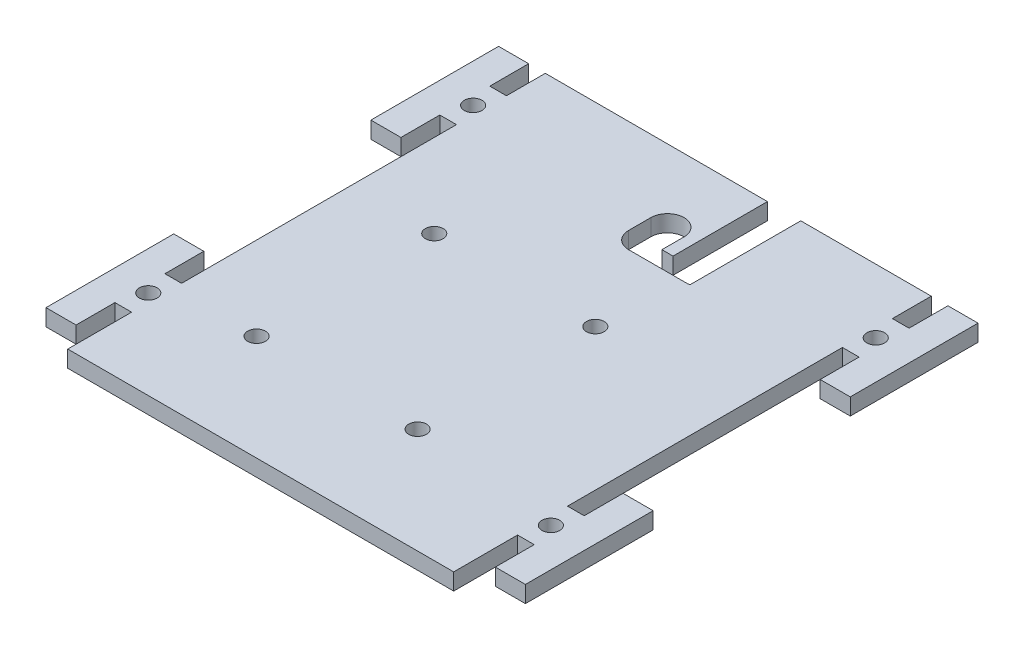
SolidWorks part; units mm, degrees
ref_plane "前视基准面" through (0, 0, 0) normal (0, 0, 1) x (1, 0, 0)
ref_plane "上视基准面" through (0, 0, 0) normal (0, 1, 0) x (1, 0, 0)
ref_plane "右视基准面" through (0, 0, 0) normal (1, 0, 0) x (0, 0, -1)
other "Configuration Table"
sketch "草图1" plane through (0, 0, 0) normal (0, 1, 0) x (1, 0, 0)
  line L0 (-25.4238, 10.5123) -> (44.0762, 10.5123)
  line L1 (44.0762, 10.5123) -> (44.0762, 22.0123)
  line L2 (44.0762, 22.0123) -> (47.0762, 22.0123)
  line L3 (47.0762, 22.0123) -> (47.0762, 15.0123)
  line L4 (47.0762, 15.0123) -> (52.4909, 15.0123)
  line L5 (52.4909, 15.0123) -> (52.4909, 38.0123)
  line L6 (52.4909, 38.0123) -> (47.0762, 38.0123)
  line L7 (47.0762, 38.0123) -> (47.0762, 31.0123)
  line L8 (47.0762, 31.0123) -> (44.0762, 31.0123)
  line L9 (44.0762, 31.0123) -> (44.0762, 80.5123)
  line L10 (44.0762, 80.5123) -> (47.0762, 80.5123)
  line L11 (47.0762, 80.5123) -> (47.0762, 73.5123)
  line L12 (47.0762, 73.5123) -> (52.4909, 73.5123)
  line L13 (52.4909, 73.5123) -> (52.4909, 96.5123)
  line L14 (52.4909, 96.5123) -> (47.0762, 96.5123)
  line L15 (47.0762, 96.5123) -> (47.0762, 89.5123)
  line L16 (47.0762, 89.5123) -> (44.0762, 89.5123)
  line L17 (44.0762, 89.5123) -> (44.0762, 96.5123)
  line L18 (44.0762, 96.5123) -> (20.5762, 96.5123)
  line L20 (19.9909, 76.5089) -> (9.5762, 76.5089)
  line L21 (6.5762, 79.5089) -> (6.5762, 83.5089)
  line L22 (12.5762, 83.5089) -> (12.5762, 79.5089)
  line L23 (12.5762, 79.5089) -> (14.5762, 79.5089)
  line L26 (20.5762, 96.5123) -> (20.5762, 76.5665)
  line L27 (14.5762, 79.5089) -> (14.5762, 96.5123)
  line L28 (14.5762, 96.5123) -> (-25.4238, 96.5123)
  line L29 (44.0762, 10.5123) -> (9.3262, 10.5123) construction
  line L30 (9.3262, 10.5123) -> (9.3262, 36.3757) construction
  line L31 (9.3262, 36.3757) -> (9.3262, 103.0112) construction
  line L32 (-25.4238, 31.0123) -> (-25.4238, 80.5123)
  line L33 (-25.4238, 10.5123) -> (-25.4238, 22.0123)
  line L34 (-25.4238, 22.0123) -> (-28.4238, 22.0123)
  line L35 (-28.4238, 22.0123) -> (-28.4238, 15.0123)
  line L36 (-28.4238, 15.0123) -> (-33.8386, 15.0123)
  line L37 (-33.8386, 15.0123) -> (-33.8386, 38.0123)
  line L38 (-33.8386, 38.0123) -> (-28.4238, 38.0123)
  line L39 (-28.4238, 38.0123) -> (-28.4238, 31.0123)
  line L40 (-28.4238, 31.0123) -> (-25.4238, 31.0123)
  line L41 (-28.4238, 80.5123) -> (-28.4238, 73.5123)
  line L42 (-28.4238, 73.5123) -> (-33.8386, 73.5123)
  line L43 (-25.4238, 80.5123) -> (-28.4238, 80.5123)
  line L44 (-28.4238, 89.5123) -> (-25.4238, 89.5123)
  line L45 (-33.8386, 96.5123) -> (-28.4238, 96.5123)
  line L46 (-28.4238, 96.5123) -> (-28.4238, 89.5123)
  line L47 (-33.8386, 73.5123) -> (-33.8386, 96.5123)
  line L48 (-25.4238, 96.5123) -> (-25.4238, 89.5123)
  line L49 (-25.4238, 10.5123) -> (-10.4238, 10.5123) construction
  line L50 (-10.4238, 10.5123) -> (-10.4238, 29.5123) construction
  line L51 (-10.4238, 29.5123) -> (4.0762, 29.5123) construction
  line L52 (4.0762, 29.5123) -> (4.0762, 45.5123) construction
  line L53 (4.0762, 45.5123) -> (-5.8085, 45.5123) construction
  line L54 (-28.4238, 31.0123) -> (-25.4238, 22.0123) construction
  line L55 (-25.4238, 31.0123) -> (-28.4238, 22.0123) construction
  line L56 (-25.4238, 10.5123) -> (-25.4238, 53.5123) construction
  line L57 (-25.4238, 53.5123) -> (60.3092, 53.5123) construction
  line L58 (44.0762, 89.5123) -> (47.0762, 80.5123) construction
  line L59 (47.0762, 89.5123) -> (44.0762, 80.5123) construction
  arc A0 (20.5762, 76.5665) -> (19.9909, 76.5089) centre (19.9909, 79.5089) cw
  arc A1 (9.5762, 76.5089) -> (6.5762, 79.5089) centre (9.5762, 79.5089) cw
  arc A2 (6.5762, 83.5089) -> (12.5762, 83.5089) centre (9.5762, 83.5089) cw
  circle A3 centre (-10.4238, 29.5123) radius 1.6
  circle A4 centre (18.5762, 29.5123) radius 1.6
  circle A5 centre (18.5762, 61.5123) radius 1.6
  circle A6 centre (-10.4238, 61.5123) radius 1.6
  circle A7 centre (-26.9238, 26.5123) radius 1.6
  circle A8 centre (45.5762, 26.5123) radius 1.6
  circle A9 centre (45.5762, 85.0123) radius 1.6
  circle A10 centre (-26.9238, 85.0123) radius 1.6
  dimension "D1" = 3
  dimension "D2" = 3
  dimension "D14" = 3
  dimension "D3" = 7
  dimension "D4" = 7
  dimension "D5" = 7
  dimension "D6" = 23
  dimension "D7" = 7
  dimension "D8" = 7
  dimension "D9" = 23
  dimension "D10" = 49.5
  dimension "D11" = 69.5
  dimension "D12" = 23.5
  dimension "D13" = 11.5
  dimension "D15" = 3
  dimension "D16" = 3
  dimension "D17" = 3
extrude "凸台-拉伸1" add sketch "草图1" along normal blind 3 contours L21 A2 L22 L23 L27 L28 L48 L44 L46 L45 L47 L42 L41 L43 L32 L40 L39 L38 L37 L36 L35 L34 L33 L0 L1 L2 L3 L4 L5 L6 L7 L8 L9 L10 L11 L12 L13 L14 L15 L16 L17 L18 L26 A0 L20 A1 A8 A7
